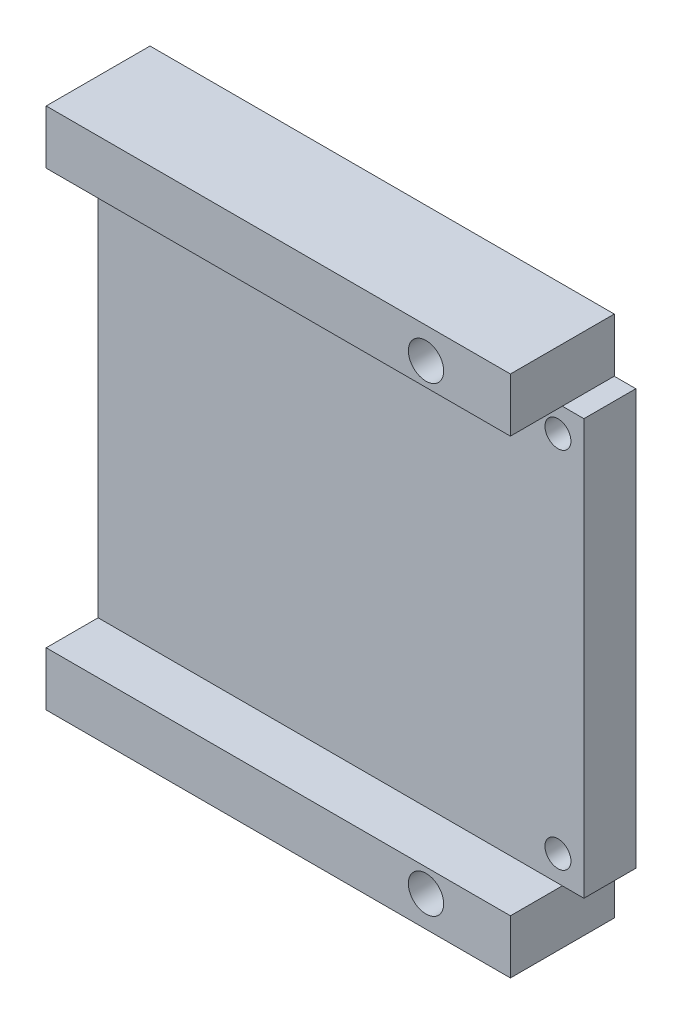
SolidWorks part; units mm, degrees
material "ABS"
ref_plane "X-Y Datum" through (0, 0, 0) normal (0, 0, 1) x (1, 0, 0)
ref_plane "X-Z Datum" through (0, 0, 0) normal (0, 1, 0) x (1, 0, 0)
ref_plane "Y-Z Datum" through (0, 0, 0) normal (1, 0, 0) x (0, 0, -1)
sketch "Sketch1" plane through (0, 0, 0) normal (0, 0, 1) x (1, 0, 0)
  line L0 (132.0402, 93.7832) -> (129.9632, 93.7862) construction
  line L1 (132.0402, 53.7832) -> (129.9632, 53.7832) construction
  line L3 (132.0402, 93.7832) -> (132.0402, 53.7832) construction
  line L5 (85.2538, 93.7832) -> (85.2538, 53.7832) construction
  line L6 (85.2538, 98.9732) -> (129.9632, 98.9732)
  line L7 (129.9632, 98.9732) -> (129.9632, 93.7862)
  line L13 (129.9632, 93.7862) -> (129.9632, 98.9732) construction
  line L14 (129.9632, 98.9732) -> (85.2538, 98.9732) construction
  line L15 (85.2538, 93.7862) -> (85.2538, 98.9732) construction
  line L16 (129.9632, 93.7862) -> (132.0402, 93.7832)
  line L18 (129.9632, 53.7832) -> (129.9632, 48.5942) construction
  line L19 (129.9632, 48.5942) -> (85.2538, 48.5942) construction
  line L20 (85.2538, 53.7832) -> (85.2538, 48.5942) construction
  line L21 (132.0402, 93.7832) -> (132.0402, 53.7832)
  line L22 (132.0402, 53.7832) -> (129.9632, 53.7832)
  line L23 (129.9632, 53.7832) -> (129.9632, 48.5942)
  line L24 (129.9632, 48.5942) -> (85.2538, 48.5942)
  line L25 (85.2538, 48.5942) -> (85.2538, 98.9732)
  circle A0 centre (129.5402, 91.2832) radius 1.25
  circle A1 centre (129.5402, 56.2545) radius 1.2503
  circle A2 centre (121.8352, 51.5642) radius 1.7
  circle A3 centre (121.8352, 96.0032) radius 1.7
extrude "Boss-Extrude1" add sketch "Sketch1" along normal blind 5
sketch "Sketch2" plane through (0, 0, 5) normal (0, 0, 1) x (1, 0, 0)
  line L0 (129.9632, 93.7862) -> (85.2538, 93.7832)
  line L1 (129.9632, 53.7832) -> (85.2538, 53.7832)
  line L2 (85.2538, 53.7832) -> (85.2538, 48.5942)
  line L3 (85.2538, 48.5942) -> (129.9632, 48.5942)
  line L4 (129.9632, 48.5942) -> (129.9632, 53.7832)
  line L5 (129.9632, 93.7862) -> (129.9632, 98.9732)
  line L6 (129.9632, 98.9732) -> (85.2538, 98.9732)
  line L7 (85.2538, 98.9732) -> (85.2538, 93.7832)
  circle A0 centre (121.8352, 96.0032) radius 1.7
  circle A1 centre (121.8352, 51.5642) radius 1.7
extrude "Boss-Extrude2" add sketch "Sketch2" along normal blind 5
